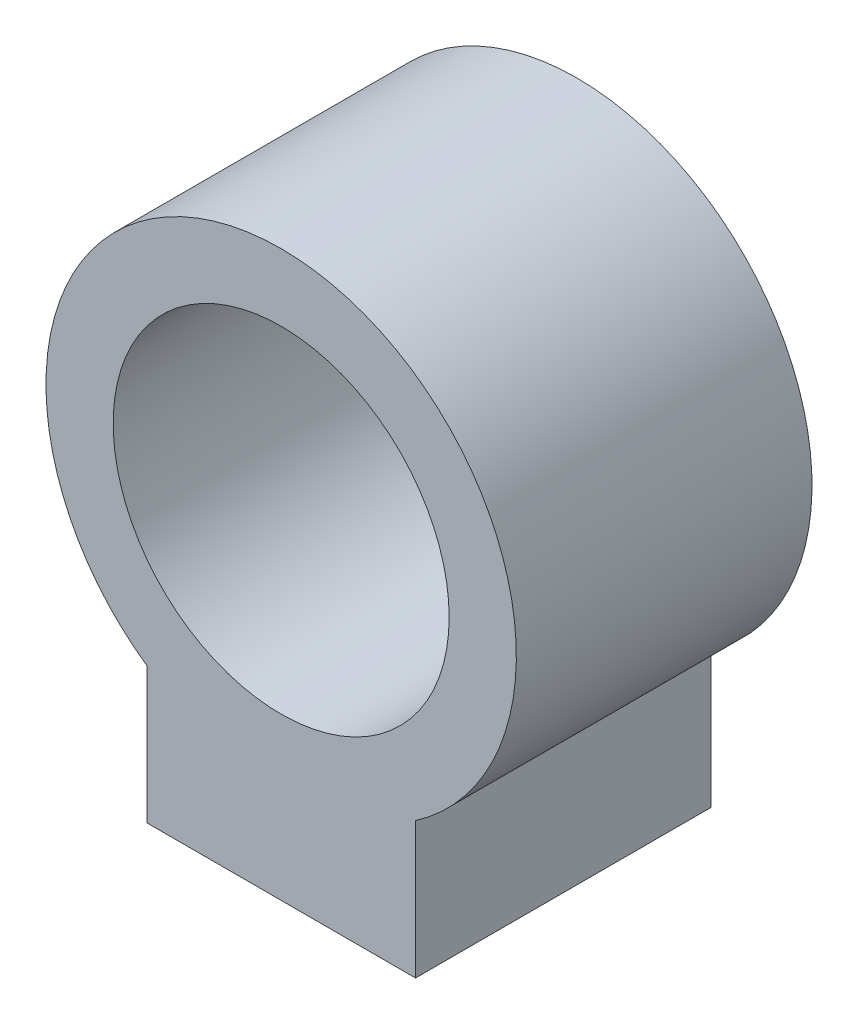
SolidWorks part; units mm, degrees
ref_plane "前视基准面" through (0, 0, 0) normal (0, 0, 1) x (1, 0, 0)
ref_plane "上视基准面" through (0, 0, 0) normal (0, 1, 0) x (1, 0, 0)
ref_plane "右视基准面" through (0, 0, 0) normal (1, 0, 0) x (0, 0, -1)
sketch "草图1" plane through (0, 0, 0) normal (0, 0, 1) x (1, 0, 0)
  line L1 (-10, 7.5) -> (10, 7.5)
  line L2 (-10, 7.5) -> (-10, -7.5)
  line L3 (-10, -7.5) -> (10, -7.5)
  line L4 (10, 7.5) -> (10, -7.5)
  line L5 (-10, 7.5) -> (10, -7.5) construction
  line L6 (-10, -7.5) -> (10, 7.5) construction
  circle A0 centre (0, 17) radius 12.5
  circle A1 centre (0, 17) radius 17.5
  point P2 (0, 0)
  dimension "D1" = 25
  dimension "D2" = 20
  dimension "D3" = 24.5
  dimension "D4" = 15
  dimension "D5" = 5
extrude "凸台-拉伸1" add sketch "草图1" along normal mid plane 22 contours L4 A1 L2 L1 A0 | A1 L2 L3 L4 | L2 A1 L4 L1
